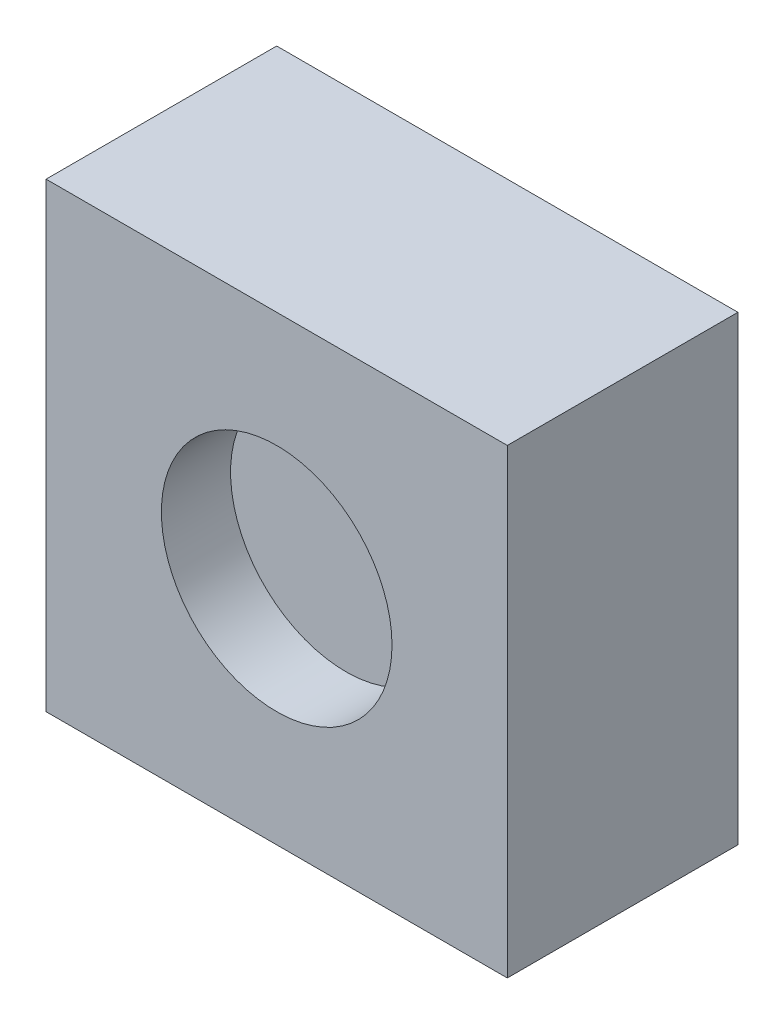
SolidWorks part; units mm, degrees
ref_plane "Front Plane" through (0, 0, 0) normal (0, 0, 1) x (1, 0, 0)
ref_plane "Top Plane" through (0, 0, 0) normal (0, 1, 0) x (1, 0, 0)
ref_plane "Right Plane" through (0, 0, 0) normal (1, 0, 0) x (0, 0, -1)
sketch "Sketch1" plane through (0, 0, 0) normal (0, 0, 1) x (1, 0, 0)
  line L1 (0, 0) -> (20, 0)
  line L2 (0, 0) -> (0, 20)
  line L3 (0, 20) -> (20, 20)
  line L4 (20, 0) -> (20, 20)
  line L5 (0, 0) -> (20, 20) construction
  line L6 (0, 20) -> (20, 0) construction
  point P4 (10, 10)
  dimension "D1" = 20
  dimension "D2" = 20
extrude "Boss-Extrude1" add sketch "Sketch1" along normal blind 10
sketch "Sketch2" plane through (0, 0, 10) normal (0, 0, 1) x (1, 0, 0)
  line L0 (20, 20) -> (0, 20) construction
  line L1 (20, 0) -> (20, 20) construction
  circle A0 centre (10, 10) radius 5
  dimension "D1" = 10
  dimension "D2" = 10
  dimension "D3" = 10
extrude "Cut-Extrude1" cut sketch "Sketch2" against normal blind 3
sketch "Sketch3" plane through (0, 0, 0) normal (0, 0, -1) x (-1, 0, 0)
  line L1 (-20, 0) -> (-20, 20) construction
  line L2 (-20, 20) -> (0, 20) construction
  line L3 (0, 0) -> (-20, 0) construction
  circle A0 centre (-13.9, 13.9) radius 2
  circle A1 centre (-6.1, 13.9) radius 2
  circle A2 centre (-13.9, 6.1) radius 2
  circle A3 centre (-6.1, 6.1) radius 2
  dimension "D1" = 4
  dimension "D2" = 4
  dimension "D3" = 4
  dimension "D4" = 4
  dimension "D5" = 7.8
  dimension "D6" = 7.8
  dimension "D7" = 7.8
  dimension "D8" = 7.8
  dimension "D9" = 6.1
  dimension "D10" = 6.1
  dimension "D11" = 6.1
  dimension "D12" = 6.1
extrude "Cut-Extrude2" cut sketch "Sketch3" against normal blind 3
